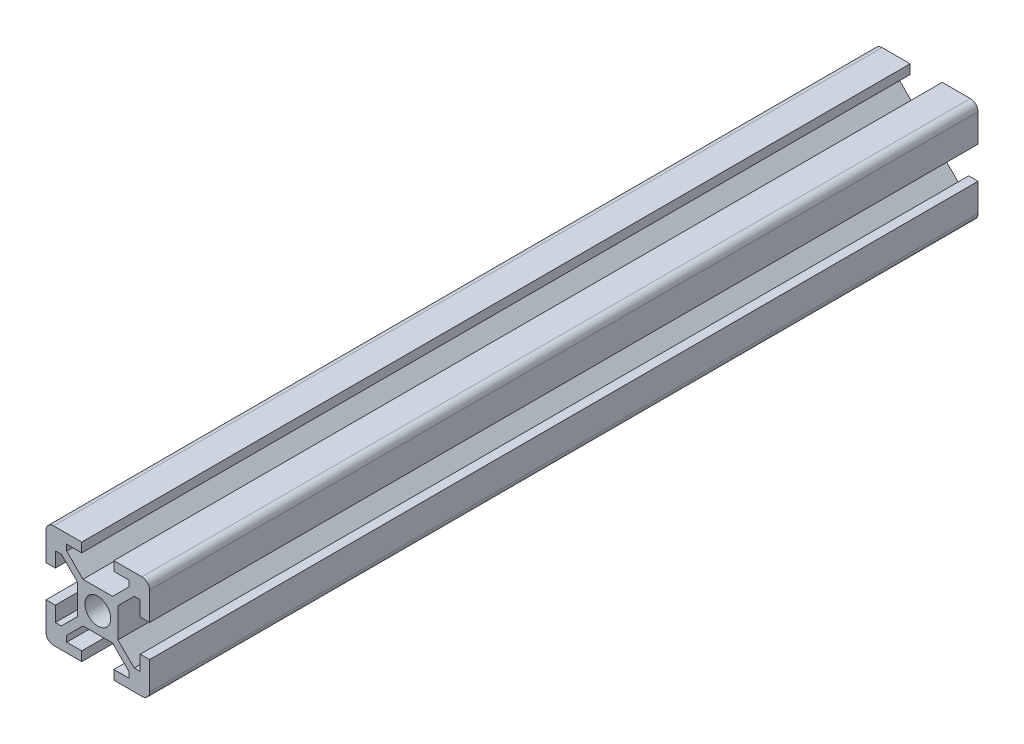
SolidWorks part; units mm, degrees
ref_plane "Front Plane" through (0, 0, 0) normal (0, 0, 1) x (1, 0, 0)
ref_plane "Top Plane" through (0, 0, 0) normal (0, 1, 0) x (1, 0, 0)
ref_plane "Right Plane" through (0, 0, 0) normal (1, 0, 0) x (0, 0, -1)
sketch "Sketch1" plane through (0, 0, 0) normal (0, 0, 1) x (1, 0, 0)
  line L0 (2.8606, 3.9) -> (6, 7.0394)
  line L5 (0, 3.9) -> (2.8606, 3.9)
  line L8 (3.9, 2.8606) -> (3.9, 0)
  line L9 (3.9, 0) -> (3.9, -2.8606)
  line L10 (3.9, -2.8606) -> (7.0394, -6)
  line L11 (6, 7.0394) -> (6, 8.2)
  line L12 (6, 8.2) -> (3.1, 8.2)
  line L13 (3.1, 8.2) -> (3.1, 10)
  line L14 (3.1, 10) -> (10, 10)
  line L15 (10, 10) -> (10, 3.1)
  line L16 (10, 3.1) -> (8.2, 3.1)
  line L17 (8.2, 3.1) -> (8.2, 6)
  line L18 (8.2, 6) -> (7.0394, 6)
  line L19 (7.0394, 6) -> (3.9, 2.8606)
  line L22 (7.0394, -6) -> (8.2, -6)
  line L23 (8.2, -6) -> (8.2, -3.1)
  line L24 (8.2, -3.1) -> (10, -3.1)
  line L25 (10, -3.1) -> (10, -10)
  line L26 (10, -10) -> (3.1, -10)
  line L27 (3.1, -10) -> (3.1, -8.2)
  line L28 (3.1, -8.2) -> (6, -8.2)
  line L29 (6, -8.2) -> (6, -7.0394)
  line L30 (6, -7.0394) -> (2.8606, -3.9)
  line L31 (2.8606, -3.9) -> (0, -3.9)
  line L32 (0, -3.9) -> (-2.8606, -3.9)
  line L33 (-2.8606, -3.9) -> (-6, -7.0394)
  line L34 (-6, -7.0394) -> (-6, -8.2)
  line L35 (-6, -8.2) -> (-3.1, -8.2)
  line L36 (-3.1, -8.2) -> (-3.1, -10)
  line L37 (-3.1, -10) -> (-10, -10)
  line L38 (-10, -10) -> (-10, -3.1)
  line L39 (-10, -3.1) -> (-8.2, -3.1)
  line L40 (-8.2, -3.1) -> (-8.2, -6)
  line L41 (-8.2, -6) -> (-7.0394, -6)
  line L42 (-7.0394, -6) -> (-3.9, -2.8606)
  line L43 (-3.9, -2.8606) -> (-3.9, 0)
  line L44 (-3.9, 0) -> (-3.9, 2.8606)
  line L45 (-3.9, 2.8606) -> (-7.0394, 6)
  line L46 (-7.0394, 6) -> (-8.2, 6)
  line L47 (-8.2, 6) -> (-8.2, 3.1)
  line L48 (-8.2, 3.1) -> (-10, 3.1)
  line L49 (-10, 3.1) -> (-10, 10)
  line L50 (-10, 10) -> (-3.1, 10)
  line L51 (-3.1, 10) -> (-3.1, 8.2)
  line L52 (-3.1, 8.2) -> (-6, 8.2)
  line L53 (-6, 8.2) -> (-6, 7.0394)
  line L54 (-6, 7.0394) -> (-2.8606, 3.9)
  line L55 (-2.8606, 3.9) -> (0, 3.9)
  circle A0 centre (0, 0) radius 2.5
  point P0 (0, 0)
  dimension "D9" = 5
  dimension "D1" = 45
  dimension "D2" = 10
  dimension "D3" = 6.1
  dimension "D4" = 3.1
  dimension "D5" = 1.47
  dimension "D6" = 4.3
  dimension "D7" = 6
  dimension "D8" = 4
extrude "Boss-Extrude1" add sketch "Sketch1" along normal blind 160
fillet "Fillet1" radius 1.47 4 edges at (-10, -10, 80) (-10, 10, 80) (10, -10, 80) (10, 10, 80)
sketch "Sketch2" plane through (3.9, 0, 0) normal (1, 0, 0) x (0, 0, -1)
  circle A0 centre (-150, 0) radius 1.5
  circle A1 centre (-79.29, 0) radius 1.5
  circle A2 centre (-10, 0) radius 1.5
  point P6 (0, 0)
  dimension "D1" = 3
  dimension "D2" = 3
  dimension "D3" = 3
  dimension "D4" = 10
  dimension "D5" = 69.29
  dimension "D6" = 70.71
extrude "Cut-Extrude1" cut sketch "Sketch2" against normal through all
